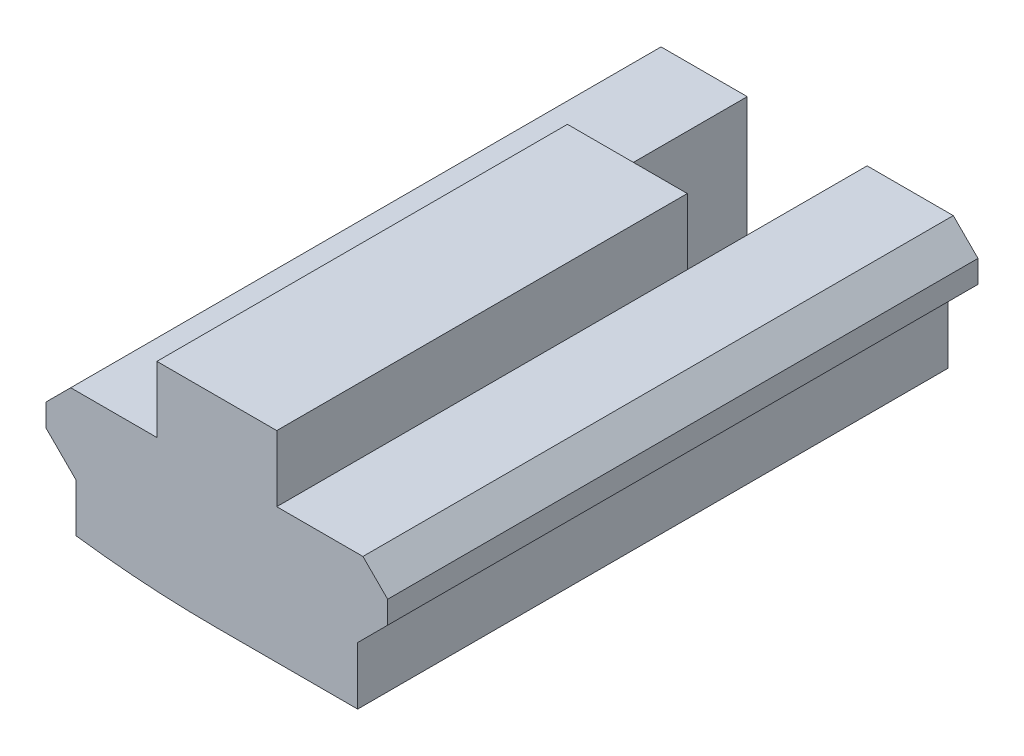
SolidWorks part; units mm, degrees
ref_plane "Front Plane" through (0, 0, 0) normal (0, 0, 1) x (1, 0, 0)
ref_plane "Top Plane" through (0, 0, 0) normal (0, 1, 0) x (1, 0, 0)
ref_plane "Right Plane" through (0, 0, 0) normal (1, 0, 0) x (0, 0, -1)
sketch "Sketch1" plane through (0, 0, 0) normal (0, 0, 1) x (1, 0, 0)
  line L91 (-115.3, 0) -> (-120, 0)
  line L92 (-120, 6.7) -> (-120, 0) construction
  line L104 (-122, 4.5) -> (-124.8757, 4.5)
  line L105 (-124.8757, 4.5) -> (-125.7, 3.6757)
  line L106 (-125.7, 3.6757) -> (-125.7, 2.9243)
  line L107 (-125.7, 2.9243) -> (-124.7, 1.9243)
  line L108 (-124.7, 1.9243) -> (-124.7, 0.3114)
  line L109 (-115.3, 0) -> (-115.3, 1.9243)
  line L110 (-115.3, 1.9243) -> (-114.3, 2.9243)
  line L111 (-114.3, 2.9243) -> (-114.3, 3.6757)
  line L112 (-114.3, 3.6757) -> (-115.1243, 4.5)
  line L113 (-115.1243, 4.5) -> (-118, 4.5)
  line L114 (-118, 4.5) -> (-118, 6.7)
  line L115 (-118, 6.7) -> (-122, 6.7)
  line L116 (-122, 6.7) -> (-122, 4.5)
  line L117 (-122, 4.5) -> (-124.8757, 4.5)
  line L118 (-124.8757, 4.5) -> (-125.7, 3.6757)
  line L119 (-125.7, 3.6757) -> (-125.7, 2.9243)
  line L120 (-125.7, 2.9243) -> (-124.7, 1.9243)
  line L121 (-124.7, 1.9243) -> (-124.7, 0.3114)
  line L122 (-115.3, 0) -> (-115.3, 1.9243)
  line L123 (-115.3, 1.9243) -> (-114.3, 2.9243)
  line L124 (-114.3, 2.9243) -> (-114.3, 3.6757)
  line L125 (-114.3, 3.6757) -> (-115.1243, 4.5)
  line L126 (-115.1243, 4.5) -> (-118, 4.5)
  line L127 (-118, 4.5) -> (-118, 6.7)
  line L128 (-118, 6.7) -> (-122, 6.7)
  line L129 (-122, 6.7) -> (-122, 4.5)
  arc A0 (-120, 0) -> (-124.7, 0.3114) centre (-120, 35.6272) cw
  dimension "D1" = 0.3
extrude "Boss-Extrude1" add sketch "Sketch1" against normal blind 19.7
sketch "Sketch2" plane through (0, 6.7, 0) normal (0, 1, 0) x (1, 0, 0)
  line L0 (-118, 19.7) -> (-118, 0) construction
  line L1 (-122, 19.7) -> (-118, 19.7)
  line L2 (-122, 19.7) -> (-122, 13.7)
  line L3 (-122, 13.7) -> (-118, 13.7)
  line L4 (-118, 19.7) -> (-118, 13.7)
  dimension "D1" = 6
extrude "Cut-Extrude1" cut sketch "Sketch2" against normal through all both and the other way through all
